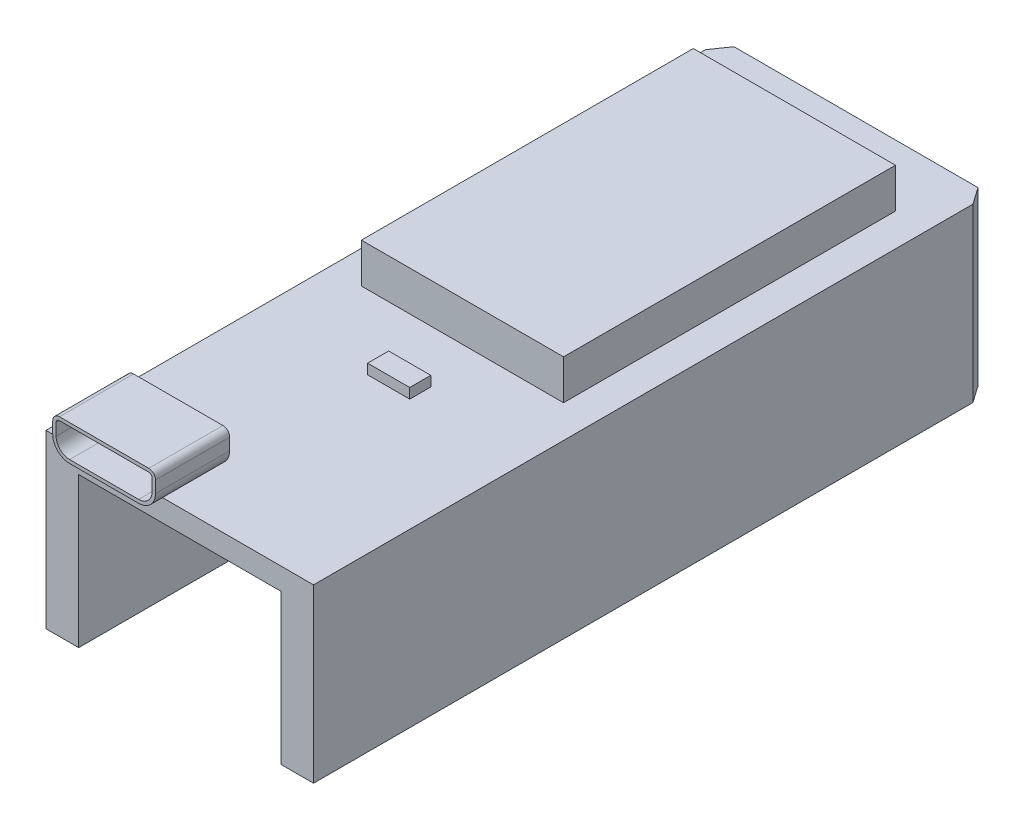
SolidWorks part; units mm, degrees
ref_plane "Front Plane" through (0, 0, 0) normal (0, 0, 1) x (1, 0, 0)
ref_plane "Top Plane" through (0, 0, 0) normal (0, 1, 0) x (1, 0, 0)
ref_plane "Right Plane" through (0, 0, 0) normal (1, 0, 0) x (0, 0, -1)
sketch "Sketch1" plane through (0, 0, 0) normal (0, 0, 1) x (1, 0, 0)
  line L0 (0, 0) -> (2.4638, 0)
  line L1 (2.4638, 0) -> (2.4638, 11.303)
  line L2 (2.4638, 11.303) -> (17.7038, 11.303)
  line L3 (17.7038, 11.303) -> (17.7038, 0)
  line L4 (17.7038, 0) -> (20.1676, 0)
  line L5 (20.1676, 0) -> (20.1676, 12.954)
  line L6 (20.1676, 12.954) -> (0, 12.954)
  line L7 (0, 12.954) -> (0, 0)
  dimension "D1" = 15.24
  dimension "D2" = 2.4638
  dimension "D3" = 2.4638
  dimension "D4" = 1.651
  dimension "D5" = 12.954
extrude "Boss-Extrude1" add sketch "Sketch1" along normal blind 50.9778
chamfer "Chamfer1" distance 0.889 angle 55 2 edges at (0, 6.477, 0) (20.1676, 6.477, 0)
sketch "Sketch2" plane through (0, 0, 50.9778) normal (0, 0, 1) x (1, 0, 0)
  line L0 (3.048, 12.954) -> (8.255, 12.954)
  line L1 (20.1676, 12.954) -> (0, 12.954) construction
  line L2 (1.778, 14.224) -> (1.778, 15.113)
  line L3 (2.286, 15.621) -> (9.017, 15.621)
  line L4 (9.525, 15.113) -> (9.525, 14.224)
  line L5 (0, 12.954) -> (0, 0) construction
  arc A0 (9.525, 14.224) -> (8.255, 12.954) centre (8.255, 14.224) cw
  arc A1 (3.048, 12.954) -> (1.778, 14.224) centre (3.048, 14.224) cw
  arc A2 (9.017, 15.621) -> (9.525, 15.113) centre (9.017, 15.113) cw
  arc A3 (1.778, 15.113) -> (2.286, 15.621) centre (2.286, 15.113) cw
  point P12 (9.525, 12.954)
  point P15 (1.778, 12.954)
  point P18 (9.525, 15.621)
  point P21 (1.778, 15.621)
  dimension "D4" = 1.27
  dimension "D5" = 0.508
  dimension "D1" = 7.747
  dimension "D2" = 2.667
  dimension "D3" = 1.778
extrude "Boss-Extrude2" add sketch "Sketch2" against normal blind 4.318 and the other way blind 1.27
sketch "Sketch3" plane through (0, 0, 52.2478) normal (0, 0, 1) x (1, 0, 0)
  line L28 (9.271, 14.224) -> (9.271, 15.113)
  line L29 (3.048, 13.208) -> (8.255, 13.208)
  line L30 (2.032, 15.113) -> (2.032, 14.224)
  line L31 (9.017, 15.367) -> (2.286, 15.367)
  line L32 (9.271, 14.224) -> (9.271, 15.113)
  line L33 (3.048, 13.208) -> (8.255, 13.208)
  line L34 (2.032, 15.113) -> (2.032, 14.224)
  line L35 (9.017, 15.367) -> (2.286, 15.367)
  arc A23 (9.271, 15.113) -> (9.017, 15.367) centre (9.017, 15.113) ccw
  arc A24 (8.255, 13.208) -> (9.271, 14.224) centre (8.255, 14.224) ccw
  arc A25 (2.032, 14.224) -> (3.048, 13.208) centre (3.048, 14.224) ccw
  arc A26 (2.286, 15.367) -> (2.032, 15.113) centre (2.286, 15.113) ccw
  arc A27 (9.271, 15.113) -> (9.017, 15.367) centre (9.017, 15.113) ccw
  arc A28 (8.255, 13.208) -> (9.271, 14.224) centre (8.255, 14.224) ccw
  arc A29 (2.032, 14.224) -> (3.048, 13.208) centre (3.048, 14.224) ccw
  arc A30 (2.286, 15.367) -> (2.032, 15.113) centre (2.286, 15.113) ccw
  dimension "D1" = 0.254
extrude "Cut-Extrude1" cut sketch "Sketch3" against normal blind 5.08
sketch "Sketch4" plane through (0, 12.954, 0) normal (0, 1, 0) x (1, 0, 0)
  line L0 (20.1676, -50.9778) -> (8.255, -50.9778) construction
  line L1 (8.4963, -33.6423) -> (11.6713, -33.6423)
  line L2 (8.4963, -33.6423) -> (8.4963, -35.2298)
  line L3 (8.4963, -35.2298) -> (11.6713, -35.2298)
  line L4 (11.6713, -33.6423) -> (11.6713, -35.2298)
  line L5 (10.0838, 0) -> (10.0838, -50.9778) construction
  line L6 (19.2786, 0) -> (0.889, 0) construction
  line L7 (8.4963, -34.436) -> (0, -34.436) construction
  line L8 (0, -50.9778) -> (0, -1.2696) construction
  line L9 (11.6713, -34.436) -> (20.1676, -34.436) construction
  line L10 (20.1676, -50.9778) -> (20.1676, -1.2696) construction
  point P6 (14.2113, -50.9778)
  dimension "D1" = 1.5875
  dimension "D2" = 3.175
  dimension "D3" = 15.748
extrude "Boss-Extrude3" add sketch "Sketch4" along normal blind 0.762
sketch "Sketch5" plane through (0, 12.954, 0) normal (0, 1, 0) x (1, 0, 0)
  line L0 (2.4638, -17.1577) -> (0, -17.1577) construction
  line L1 (2.4638, -4.6482) -> (17.7038, -4.6482)
  line L2 (2.4638, -4.6482) -> (2.4638, -29.6672)
  line L3 (2.4638, -29.6672) -> (17.7038, -29.6672)
  line L4 (17.7038, -4.6482) -> (17.7038, -29.6672)
  line L5 (0, -50.9778) -> (0, -1.2696) construction
  line L6 (17.7038, -17.1577) -> (20.1676, -17.1577) construction
  line L7 (20.1676, -50.9778) -> (20.1676, -1.2696) construction
  line L8 (19.2786, 0) -> (0.889, 0) construction
  dimension "D1" = 15.24
  dimension "D2" = 25.019
  dimension "D3" = 4.6482
extrude "Boss-Extrude4" add sketch "Sketch5" along normal blind 2.9972
